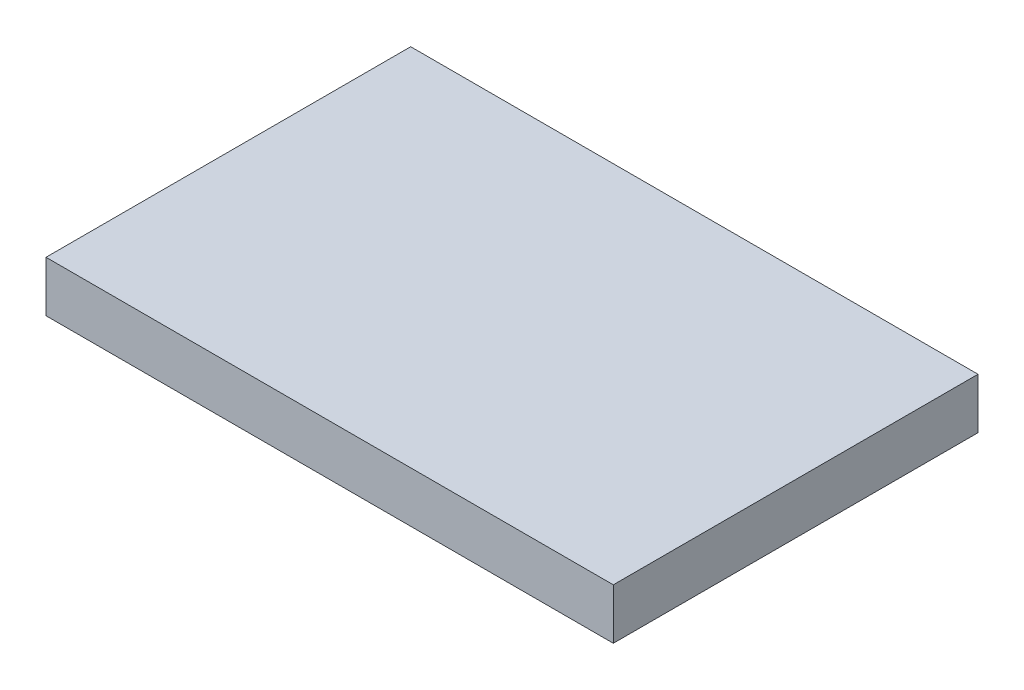
SolidWorks part; units mm, degrees
ref_plane "Front Plane" through (0, 0, 0) normal (0, 0, 1) x (1, 0, 0)
ref_plane "Top Plane" through (0, 0, 0) normal (0, 1, 0) x (1, 0, 0)
ref_plane "Right Plane" through (0, 0, 0) normal (1, 0, 0) x (0, 0, -1)
sketch "Sketch1" plane through (0, 0, 0) normal (0, 1, 0) x (1, 0, 0)
  line L1 (0, 0) -> (28, 0)
  line L2 (0, 0) -> (0, 18)
  line L3 (0, 18) -> (28, 18)
  line L4 (28, 0) -> (28, 18)
  dimension "D1" = 18
  dimension "D2" = 28
extrude "Boss-Extrude1" add sketch "Sketch1" along normal blind 2.5
